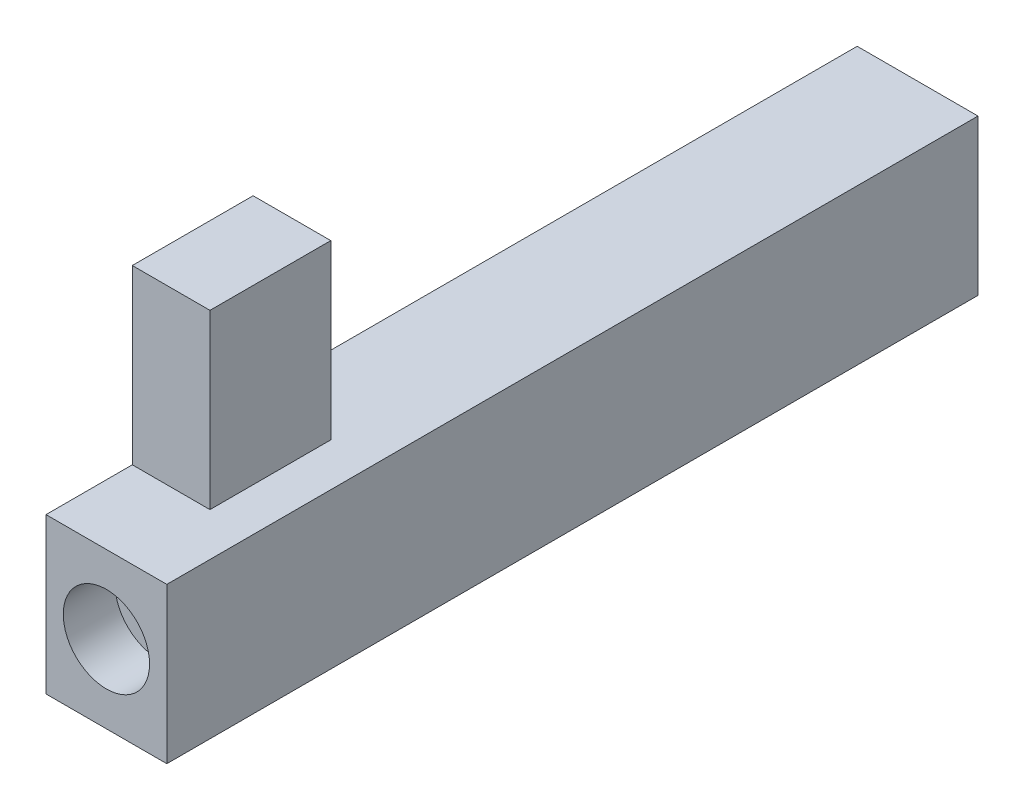
SolidWorks part; units mm, degrees
ref_plane "Alzado" through (0, 0, 0) normal (0, 0, 1) x (1, 0, 0)
ref_plane "Planta" through (0, 0, 0) normal (0, 1, 0) x (1, 0, 0)
ref_plane "Vista lateral" through (0, 0, 0) normal (1, 0, 0) x (0, 0, -1)
sketch "Croquis1" plane through (0, 0, 0) normal (0, 1, 0) x (1, 0, 0)
  line L1 (0, 0) -> (7, 0)
  line L2 (0, 0) -> (0, 47)
  line L3 (0, 47) -> (7, 47)
  line L4 (7, 0) -> (7, 47)
  dimension "D1" = 7
  dimension "D2" = 47
extrude "Saliente-Extruir1" add sketch "Croquis1" along normal blind 9
sketch "Croquis2" plane through (0, 9, 0) normal (0, 1, 0) x (1, 0, 0)
  line L0 (0, 47) -> (0, 0) construction
  line L1 (0, 12) -> (4.5, 12)
  line L2 (0, 12) -> (0, 5)
  line L3 (0, 5) -> (4.5, 5)
  line L6 (0, 0) -> (7, 0) construction
  line L7 (4.5, 12) -> (4.5, 5)
  dimension "D1" = 4.5
  dimension "D2" = 5
  dimension "D3" = 7
extrude "Saliente-Extruir2" add sketch "Croquis2" along normal blind 10
sketch "Croquis3" plane through (0, 0, 0) normal (0, 0, 1) x (1, 0, 0)
  line L0 (0, 0) -> (7, 9) construction
  circle A0 centre (3.5, 4.5) radius 1.25
  dimension "D1" = 2.5
extrude "Cortar-Extruir1" cut sketch "Croquis3" against normal blind 49
sketch "Croquis6" plane through (0, 0, 0) normal (0, 0, 1) x (1, 0, 0)
  circle A0 centre (3.5, 4.5) radius 2.5
  dimension "D1" = 5
extrude "Cortar-Extruir2" cut sketch "Croquis6" against normal blind 3
